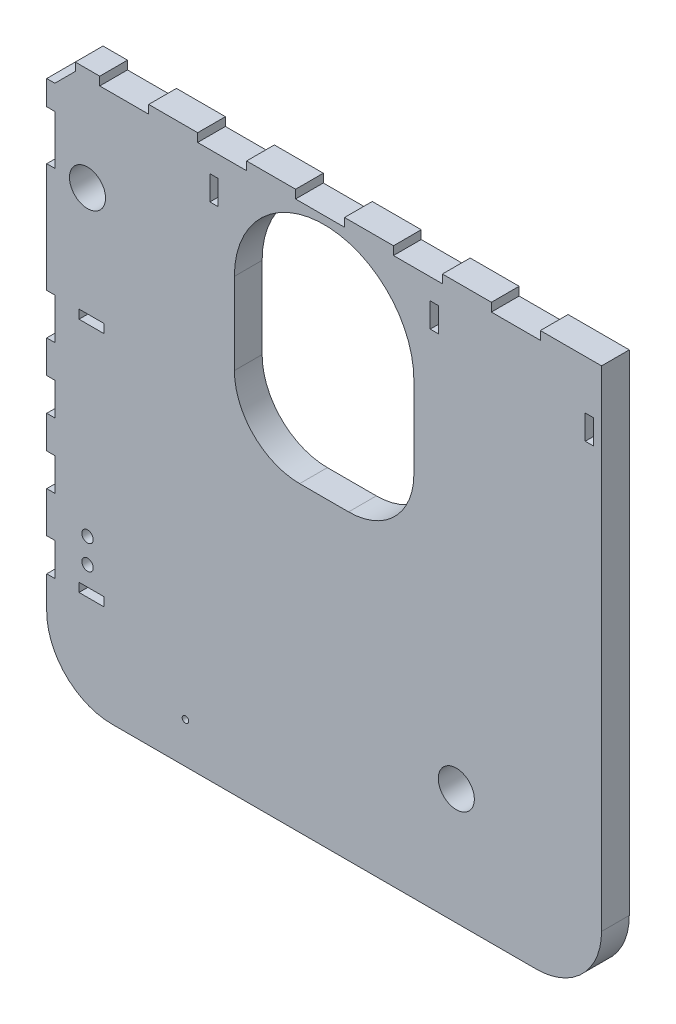
SolidWorks part; units mm, degrees
ref_plane "Front Plane" through (0, 0, 0) normal (0, 0, 1) x (1, 0, 0)
ref_plane "Top Plane" through (0, 0, 0) normal (0, 1, 0) x (1, 0, 0)
ref_plane "Right Plane" through (0, 0, 0) normal (1, 0, 0) x (0, 0, -1)
sketch "Model" plane through (0, 0, 0) normal (0, 0, 1) x (1, 0, 0)
  line L310 (60.8218, -613.4692) -> (60.8218, -563.4692)
  line L311 (-49.1782, -563.4692) -> (-49.1782, -613.4692)
  line L312 (-9.1782, -653.4692) -> (20.8218, -653.4692)
  line L313 (-158.9782, -561.1692) -> (-164.1782, -561.1692)
  line L314 (-164.1782, -561.1692) -> (-164.1782, -628.4192)
  line L315 (-164.1782, -628.4192) -> (-158.9782, -628.4192)
  line L316 (-158.9782, -628.4192) -> (-158.9782, -653.6192)
  line L317 (-158.9782, -653.6192) -> (-164.1782, -653.6192)
  line L318 (-164.1782, -653.6192) -> (-164.1782, -673.6192)
  line L319 (-164.1782, -673.6192) -> (-158.9782, -673.6192)
  line L320 (-158.9782, -673.6192) -> (-158.9782, -693.6192)
  line L321 (-158.9782, -693.6192) -> (-164.1782, -693.6192)
  line L322 (-164.1782, -693.6192) -> (-164.1782, -713.6192)
  line L323 (-164.1782, -713.6192) -> (-158.9782, -713.6192)
  line L324 (-158.9782, -713.6192) -> (-158.9782, -733.6192)
  line L325 (-158.9782, -733.6192) -> (-164.1782, -733.6192)
  line L326 (-164.1782, -733.6192) -> (-164.1782, -758.6192)
  line L327 (-164.1782, -758.6192) -> (-158.9782, -758.6192)
  line L328 (-158.9782, -758.6192) -> (-158.9782, -778.8192)
  line L329 (-158.9782, -778.8192) -> (-164.1782, -778.8192)
  line L330 (-164.1782, -778.8192) -> (-164.1782, -798.6192)
  line L331 (-124.1782, -838.6192) -> (135.8218, -838.6192)
  line L332 (175.8218, -798.6192) -> (175.8218, -498.4692)
  line L333 (175.8218, -498.4692) -> (138.3218, -498.4692)
  line L334 (138.3218, -498.4692) -> (138.3218, -503.6692)
  line L335 (138.3218, -503.6692) -> (108.3218, -503.6692)
  line L336 (108.3218, -503.6692) -> (108.3218, -498.4692)
  line L337 (108.3218, -498.4692) -> (78.3218, -498.4692)
  line L338 (78.3218, -498.4692) -> (78.3218, -503.6692)
  line L339 (78.3218, -503.6692) -> (48.3218, -503.6692)
  line L340 (48.3218, -503.6692) -> (48.3218, -498.4692)
  line L341 (48.3218, -498.4692) -> (18.3218, -498.4692)
  line L342 (18.3218, -498.4692) -> (18.3218, -503.6692)
  line L343 (18.3218, -503.6692) -> (-11.6782, -503.6692)
  line L344 (-11.6782, -503.6692) -> (-11.6782, -498.4692)
  line L345 (-11.6782, -498.4692) -> (-41.6782, -498.4692)
  line L346 (-41.6782, -498.4692) -> (-41.6782, -503.6692)
  line L347 (-41.6782, -503.6692) -> (-71.6782, -503.6692)
  line L348 (-71.6782, -503.6692) -> (-71.6782, -498.4692)
  line L349 (-71.6782, -498.4692) -> (-101.6782, -498.4692)
  line L350 (-101.6782, -498.4692) -> (-101.6782, -503.6692)
  line L351 (-101.6782, -503.6692) -> (-131.6782, -503.6692)
  line L352 (-131.6782, -503.6692) -> (-131.6782, -498.4692)
  line L353 (-131.6782, -498.4692) -> (-146.6782, -498.4692)
  line L354 (-146.6782, -498.4692) -> (-146.6782, -503.4692)
  line L355 (-146.6782, -503.4692) -> (-159.1782, -515.9692)
  line L356 (-159.1782, -515.9692) -> (-164.1782, -515.9692)
  line L357 (-164.1782, -515.9692) -> (-164.1782, -530.9692)
  line L358 (-164.1782, -530.9692) -> (-158.9782, -530.9692)
  line L359 (-158.9782, -530.9692) -> (-158.9782, -561.1692)
  line L360 (-144.3782, -633.8192) -> (-144.3782, -628.4192)
  line L361 (-144.3782, -628.4192) -> (-128.9782, -628.4192)
  line L362 (-128.9782, -628.4192) -> (-128.9782, -633.8192)
  line L363 (-128.9782, -633.8192) -> (-144.3782, -633.8192)
  line L364 (-144.3782, -778.8192) -> (-144.3782, -773.4192)
  line L365 (-144.3782, -773.4192) -> (-128.9782, -773.4192)
  line L366 (-128.9782, -773.4192) -> (-128.9782, -778.8192)
  line L367 (-128.9782, -778.8192) -> (-144.3782, -778.8192)
  line L368 (70.8218, -531.4692) -> (70.8218, -516.4692)
  line L369 (70.8218, -516.4692) -> (75.8218, -516.4692)
  line L370 (75.8218, -516.4692) -> (75.8218, -531.4692)
  line L371 (75.8218, -531.4692) -> (70.8218, -531.4692)
  line L372 (165.8218, -543.4692) -> (165.8218, -528.4692)
  line L373 (165.8218, -528.4692) -> (170.8218, -528.4692)
  line L374 (170.8218, -528.4692) -> (170.8218, -543.4692)
  line L375 (170.8218, -543.4692) -> (165.8218, -543.4692)
  line L376 (-59.1782, -531.4692) -> (-59.1782, -516.4692)
  line L377 (-59.1782, -516.4692) -> (-64.1782, -516.4692)
  line L378 (-64.1782, -516.4692) -> (-64.1782, -531.4692)
  line L379 (-64.1782, -531.4692) -> (-59.1782, -531.4692)
  arc A335 (20.8218, -653.4692) -> (60.8218, -613.4692) centre (20.8218, -613.4692) ccw
  arc A336 (60.8218, -563.4692) -> (-49.1782, -563.4692) centre (5.8218, -563.4692) ccw
  arc A337 (-49.1782, -613.4692) -> (-9.1782, -653.4692) centre (-9.1782, -613.4692) ccw
  arc A338 (-164.1782, -798.6192) -> (-124.1782, -838.6192) centre (-124.1782, -798.6192) ccw
  arc A339 (135.8218, -838.6192) -> (175.8218, -798.6192) centre (135.8218, -798.6192) ccw
  circle A340 centre (86.8218, -767.4692) radius 11.05
  circle A341 centre (-139.1782, -561.4692) radius 11.05
  circle A342 centre (-79.1782, -813.6192) radius 2
  circle A343 centre (-139.1782, -746.4692) radius 3.5
  circle A344 centre (-139.1782, -761.4692) radius 3.5
extrude "Boss-Extrude1" add sketch "Model" along normal blind 17
